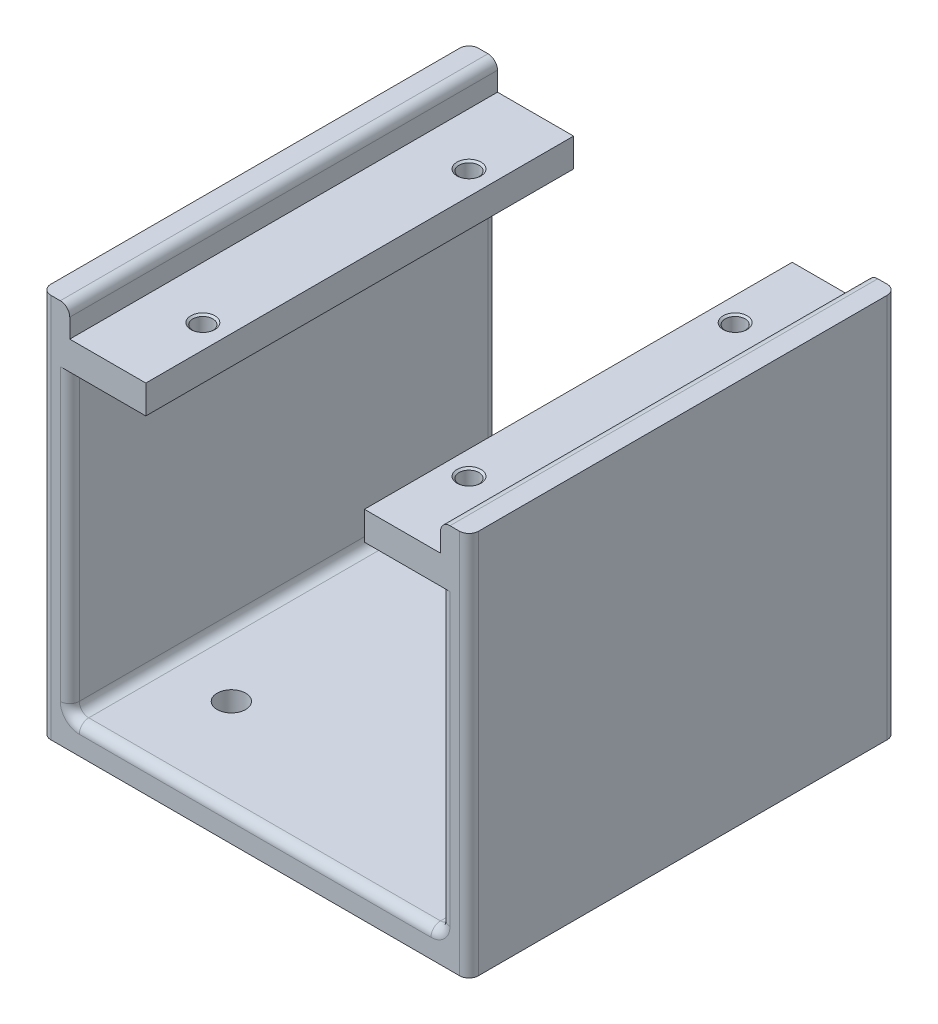
SolidWorks part; units mm, degrees
ref_plane "Front Plane" through (0, 0, 0) normal (0, 0, 1) x (1, 0, 0)
ref_plane "Top Plane" through (0, 0, 0) normal (0, 1, 0) x (1, 0, 0)
ref_plane "Right Plane" through (0, 0, 0) normal (1, 0, 0) x (0, 0, -1)
sketch "Sketch2" plane through (0, 0, 0) normal (0, 1, 0) x (1, 0, 0)
  line L1 (-45, -45) -> (45, -45)
  line L2 (-45, -45) -> (-45, 45)
  line L3 (-45, 45) -> (45, 45)
  line L4 (45, -45) -> (45, 45)
  line L5 (-45, -45) -> (45, 45) construction
  line L6 (-45, 45) -> (45, -45) construction
  point P0 (0, 0)
  dimension "D1" = 90
  dimension "D2" = 90
extrude "Boss-Extrude1" add sketch "Sketch2" along normal blind 6
sketch "Sketch3" plane through (0, 6, 0) normal (0, 1, 0) x (1, 0, 0)
  line L0 (-45, -45) -> (45, -45) construction
  line L1 (-45, 45) -> (-39, 45)
  line L2 (-45, 45) -> (-45, -45)
  line L3 (-45, -45) -> (-39, -45)
  line L4 (-39, 45) -> (-39, -45)
  line L6 (45, 45) -> (39, 45)
  line L7 (45, 45) -> (45, -45)
  line L8 (45, -45) -> (39, -45)
  line L9 (39, 45) -> (39, -45)
  dimension "D1" = 6
  dimension "D2" = 6
extrude "Boss-Extrude2" add sketch "Sketch3" along normal blind 75
sketch "Sketch5" plane through (-39, 0, 0) normal (1, 0, 0) x (0, 0, -1)
  line L0 (45, 81) -> (45, 0) construction
  line L1 (-45, 75) -> (45, 75)
  line L2 (-45, 75) -> (-45, 69)
  line L3 (-45, 69) -> (45, 69)
  line L4 (45, 75) -> (45, 69)
  dimension "D1" = 6
  dimension "D2" = 75
extrude "Boss-Extrude3" add sketch "Sketch5" along normal blind 16
sketch "Sketch6" plane through (39, 0, 0) normal (-1, 0, 0) x (0, 0, 1)
  line L0 (45, 81) -> (45, 0) construction
  line L1 (-45, 75) -> (45, 75)
  line L2 (-45, 75) -> (-45, 69)
  line L3 (-45, 69) -> (45, 69)
  line L4 (45, 75) -> (45, 69)
  line L5 (-45, 0) -> (45, 0) construction
  dimension "D1" = 6
  dimension "D2" = 75
extrude "Boss-Extrude4" add sketch "Sketch6" along normal blind 16
sketch "Sketch7" plane through (0, 0, 0) normal (0, -1, 0) x (1, 0, 0)
  line L0 (-45, 0) -> (45, 0) construction
  line L1 (-45, -45) -> (-45, 45) construction
  line L2 (45, 45) -> (45, -45) construction
  line L3 (0, 45) -> (0, -45) construction
  line L4 (-45, 45) -> (45, 45) construction
  line L5 (45, -45) -> (-45, -45) construction
  circle A0 centre (-25, 25) radius 3
  circle A1 centre (25, 25) radius 3
  circle A2 centre (25, -25) radius 3
  circle A3 centre (-25, -25) radius 3
  dimension "D1" = 6
  dimension "D2" = 25
  dimension "D3" = 25
extrude "Cut-Extrude1" cut sketch "Sketch7" against normal up to next
sketch "Sketch10" plane through (0, 75, 0) normal (0, 1, 0) x (1, 0, 0)
  line L0 (0, 0) -> (0, 32.9641) construction
  line L1 (0, 0) -> (30.5202, 0) construction
  point P0 (-28, 28)
  point P4 (0, 0)
  point P6 (-28, -28)
  point P7 (0, 0)
  point P8 (28, -28)
  point P9 (28, 28)
  dimension "D1" = 28
  dimension "D2" = 28
hole_wizard "M5x0.8 Tapped Hole2" positions "Sketch10" profile "Sketch11" tap size "M5x0.8" standard "ANSI Metric"
sketch "Sketch11" plane through (-28, 75, -28) normal (1, 0, 0) x (0, 0, 1)
  line L0 (0, 0) -> (0, 6)
  line L1 (0, 6) -> (2.1, 6)
  line L2 (2.1, 6) -> (2.1, 0.3566)
  line L3 (2.1, 0.3566) -> (2.525, 0)
  line L5 (2.525, 0) -> (0, 0)
  line L6 (-2.1, 0.3566) -> (-2.525, 0) construction
  line L11 (0, -6.35) -> (0, 107.95) construction
  dimension "Thru Tap Drill Dia." = 4.2
  dimension "Thru Tap Drill Depth" = 6
  dimension "Near C'Sink Dia." = 5.05
  dimension "Near C'Sink Angle" = 100
cosmetic thread "Hole Thread5" parameters "D2"=5
cosmetic thread "Hole Thread6" parameters "D2"=5
cosmetic thread "Hole Thread7" parameters "D2"=5
cosmetic thread "Hole Thread8" parameters "D2"=5
fillet "Fillet2" radius 2 14 edges at (-39, 37.5, 45) (39, 37.5, 45) (-39, 6, 0) (0, 6, 45) (39, 6, 0) (39, 81, 0) (-39, 81, 0) (-45, 40.5, 45) (-45, 40.5, -45) (45, 40.5, 45) (45, 40.5, -45) (-39, 37.5, -45) (0, 6, -45) (39, 37.5, -45)
